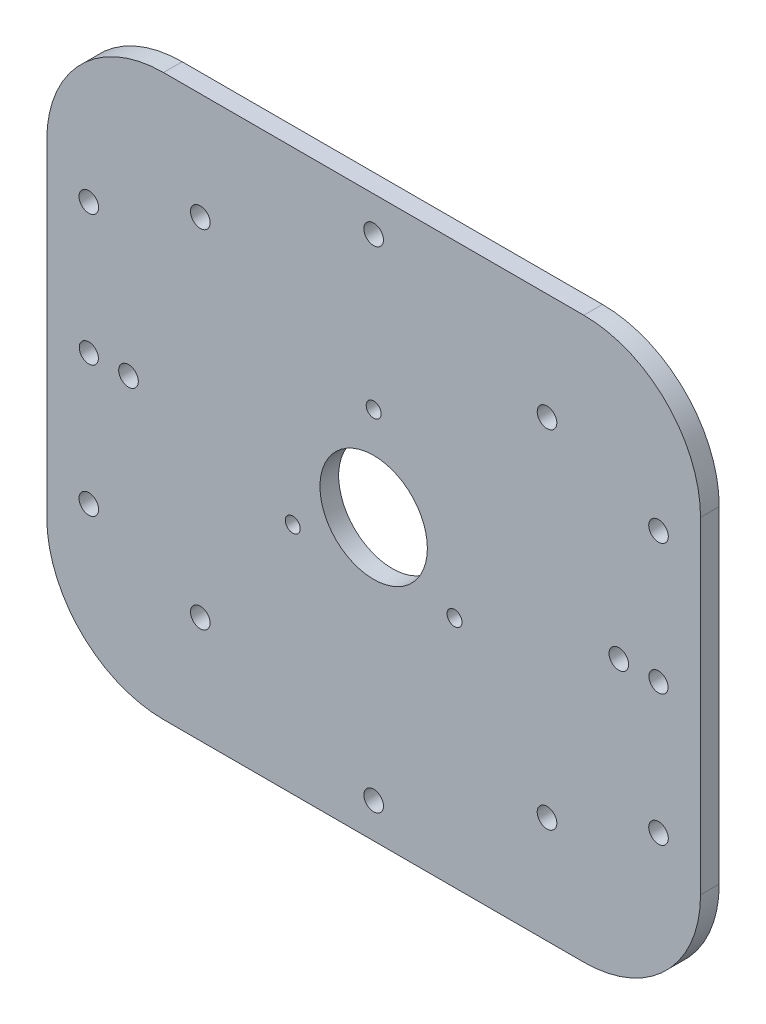
SolidWorks part; units mm, degrees
material "6061 合金"
ref_plane "前视基准面" through (0, 0, 0) normal (0, 0, 1) x (1, 0, 0)
ref_plane "上视基准面" through (0, 0, 0) normal (0, 1, 0) x (1, 0, 0)
ref_plane "右视基准面" through (0, 0, 0) normal (1, 0, 0) x (0, 0, -1)
sketch "草图1" plane through (0, 0, 0) normal (0, 0, 1) x (1, 0, 0)
  line L1 (0, 0) -> (140, 0)
  line L2 (0, 0) -> (0, 120)
  line L3 (0, 120) -> (140, 120)
  line L4 (140, 0) -> (140, 120)
  circle A0 centre (70, 60) radius 11.5
  point P7 (70, 120)
  point P9 (0, 60)
  dimension "D2" = 23
  dimension "D1" = 140
  dimension "D6" = 120
extrude "凸台-拉伸1" add sketch "草图1" along normal blind 4
ref_plane "基准面4" through (0, 60, 0) normal (0, -1, 0) x (-1, 0, 0)
sketch "草图31" plane through (0, 0, 4) normal (0, 0, 1) x (1, 0, 0)
  line L0 (9, -7.105) -> (9, 120.826) construction
  line L1 (0, 120) -> (0, 0) construction
  line L2 (0, 60) -> (9, 60) construction
  line L3 (140, 120) -> (0, 120) construction
  circle A0 centre (9, 60) radius 2.05
  circle A1 centre (9, 88) radius 2.1
  dimension "D2" = 4.1
  dimension "D3" = 4.2
  dimension "D4" = 32
  dimension "D1" = 9
extrude "切除-拉伸16" cut sketch "草图31" against normal blind 10
ref_plane "基准面5" through (0, 60, 0) normal (0, 1, 0) x (1, 0, 0)
mirror "镜向1" about plane through (0, 60, 0) normal (0, 1, 0) of "切除-拉伸16"
ref_plane "基准面6" through (70, 0, 0) normal (-1, 0, 0) x (0, 0, 1)
mirror "镜向2" about plane through (70, 0, 0) normal (-1, 0, 0) of "切除-拉伸16", "镜向1"
fillet "圆角8" radius 25 4 edges at (140, 120, 2) (140, 0, 2) (0, 0, 2) (0, 120, 2)
sketch "草图32" plane through (0, 0, 4) normal (0, 0, 1) x (1, 0, 0)
  line L0 (70, 120) -> (70, 0) construction
  line L1 (115, 120) -> (25, 120) construction
  line L2 (70, 2.2) -> (70, -2.2) construction
  line L3 (0, 60) -> (140, 60) construction
  line L4 (0, 95) -> (0, 25) construction
  line L5 (140, 25) -> (140, 95) construction
  circle A0 centre (70, 60) radius 52.5 construction
  circle A1 centre (70, 112.5) radius 2.1
  circle A2 centre (107.1231, 97.1231) radius 2.1
  circle A3 centre (122.5, 60) radius 2.1
  circle A4 centre (107.1231, 22.8769) radius 2.1
  circle A5 centre (70, 7.5) radius 2.1
  circle A6 centre (32.8769, 22.8769) radius 2.1
  circle A7 centre (17.5, 60) radius 2.1
  circle A8 centre (32.8769, 97.1231) radius 2.1
  point P32 (70, 60)
  dimension "D1" = 105
  dimension "D2" = 4.2
  dimension "D3" = 8
extrude "切除-拉伸17" cut sketch "草图32" against normal blind 10
sketch "草图33" plane through (0, 0, 4) normal (0, 0, 1) x (1, 0, 0)
  circle A0 centre (70, 60) radius 20 construction
  circle A1 centre (70, 80) radius 1.6
  circle A2 centre (87.3205, 50) radius 1.6
  circle A3 centre (52.6795, 50) radius 1.6
  point P11 (70, 60)
  dimension "D1" = 40
  dimension "D2" = 3.2
  dimension "D3" = 3
extrude "切除-拉伸18" cut sketch "草图33" against normal blind 10
